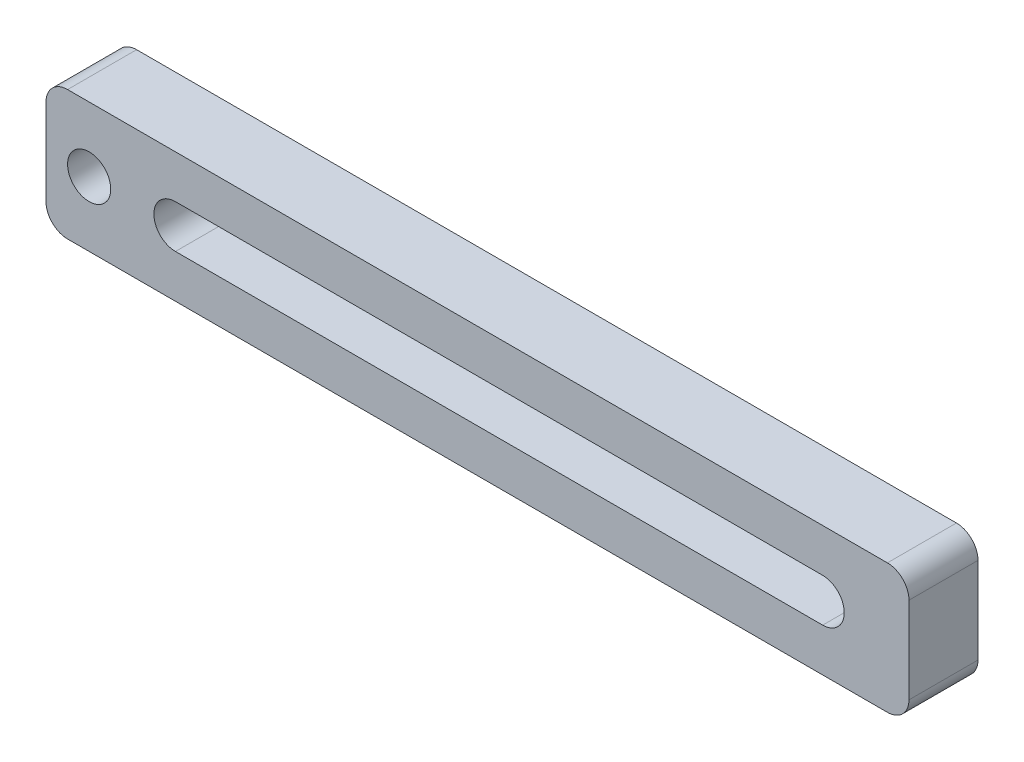
SolidWorks part; units mm, degrees
ref_plane "Спереди" through (0, 0, 0) normal (0, 0, 1) x (1, 0, 0)
ref_plane "Сверху" through (0, 0, 0) normal (0, 1, 0) x (1, 0, 0)
ref_plane "Справа" through (0, 0, 0) normal (1, 0, 0) x (0, 0, -1)
sketch "Эскиз1" plane through (0, 0, 0) normal (0, 0, 1) x (1, 0, 0)
  line L1 (0, 0) -> (100, 0)
  line L2 (0, 0) -> (0, 15)
  line L3 (0, 15) -> (100, 15)
  line L4 (100, 0) -> (100, 15)
  dimension "D1" = 100
  dimension "D2" = 15
extrude "Вытянуть1" add sketch "Эскиз1" along normal blind 8
sketch "Эскиз2" plane through (0, 0, 8) normal (0, 0, 1) x (1, 0, 0)
  line L0 (0, 15) -> (0, 0) construction
  line L1 (15, 10) -> (90, 10)
  line L3 (15, 5) -> (90, 5)
  line L4 (100, 0) -> (100, 15) construction
  line L5 (-14.6814, 7.5) -> (66.4971, 7.5) construction
  circle A0 centre (5, 7.5) radius 2.5
  arc A1 (90, 10) -> (90, 5) centre (90, 7.5) cw
  arc A2 (15, 10) -> (15, 5) centre (15, 7.5) ccw
  point P9 (0, 7.5)
  dimension "D4" = 5
  dimension "D1" = 5
  dimension "D2" = 5
  dimension "D3" = 10
  dimension "D5" = 10
extrude "Вытянуть2" cut sketch "Эскиз2" against normal blind 8
fillet "Скругление2" radius 2.5 4 edges at (0, 0, 4) (0, 15, 4) (100, 0, 4) (100, 15, 4)
